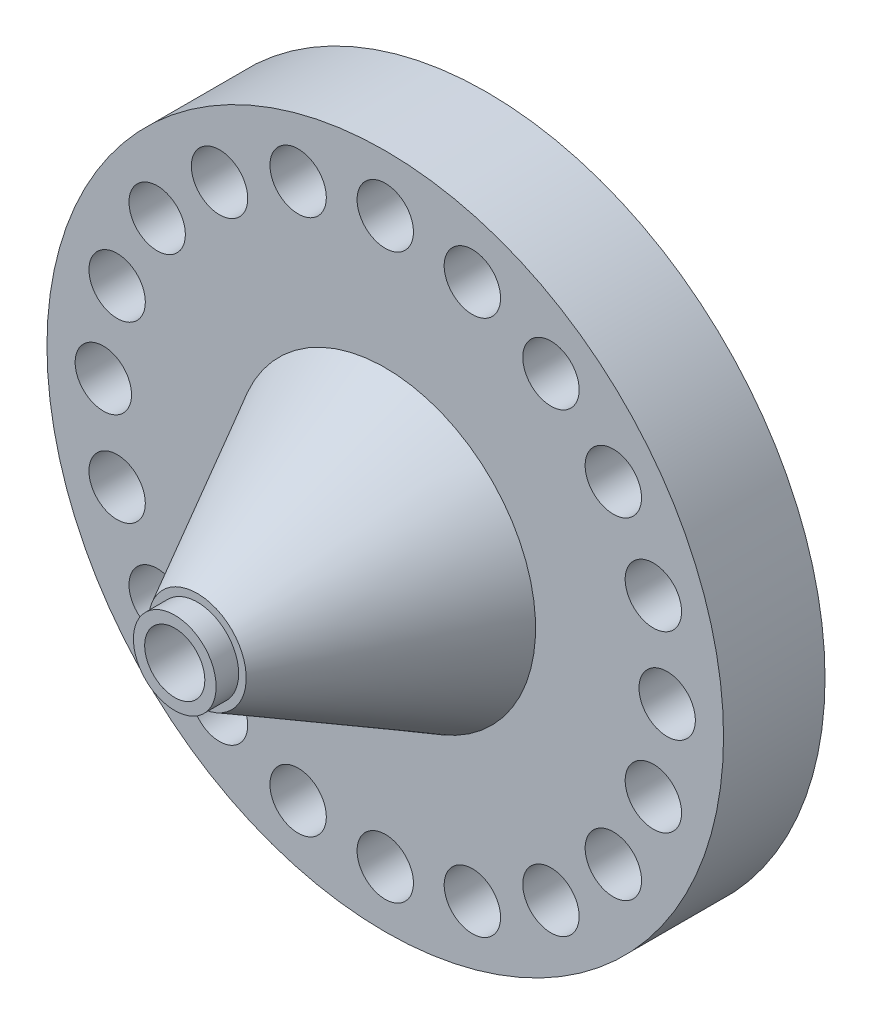
SolidWorks part; units mm, degrees
ref_plane "Front Plane" through (0, 0, 0) normal (0, 0, 1) x (1, 0, 0)
ref_plane "Top Plane" through (0, 0, 0) normal (0, 1, 0) x (1, 0, 0)
ref_plane "Right Plane" through (0, 0, 0) normal (1, 0, 0) x (0, 0, -1)
sketch "Sketch1" plane through (0, 0, 0) normal (0, 0, 1) x (1, 0, 0)
  circle A0 centre (0, 0) radius 45
  circle A1 centre (0, 0) radius 37.5 construction
  circle A2 centre (0, 37.5) radius 3.75
  circle A3 centre (11.5881, 35.6646) radius 3.75
  circle A4 centre (22.0419, 30.3381) radius 3.75
  circle A5 centre (30.3381, 22.0419) radius 3.75
  circle A6 centre (35.6646, 11.5881) radius 3.75
  circle A7 centre (37.5, 0) radius 3.75
  circle A8 centre (35.6646, -11.5881) radius 3.75
  circle A9 centre (30.3381, -22.0419) radius 3.75
  circle A10 centre (22.0419, -30.3381) radius 3.75
  circle A11 centre (11.5881, -35.6646) radius 3.75
  circle A12 centre (0, -37.5) radius 3.75
  circle A13 centre (-11.5881, -35.6646) radius 3.75
  circle A14 centre (-22.0419, -30.3381) radius 3.75
  circle A15 centre (-30.3381, -22.0419) radius 3.75
  circle A16 centre (-35.6646, -11.5881) radius 3.75
  circle A17 centre (-37.5, 0) radius 3.75
  circle A18 centre (-35.6646, 11.5881) radius 3.75
  circle A19 centre (-30.3381, 22.0419) radius 3.75
  circle A20 centre (-22.0419, 30.3381) radius 3.75
  circle A21 centre (-11.5881, 35.6646) radius 3.75
  dimension "D1" = 90
  dimension "D2" = 75
  dimension "D3" = 7.5
  dimension "D4" = 20
extrude "Boss-Extrude1" add sketch "Sketch1" along normal mid plane 13.5
sketch "Sketch2" plane through (0, 0, 6.75) normal (0, 0, 1) x (1, 0, 0)
  circle A0 centre (0, 0) radius 20
  dimension "D1" = 40
ref_plane "Plane1" through (0, 0, 31.75) normal (0, 0, 1) x (1, 0, 0)
sketch "Sketch3" plane through (0, 0, 31.75) normal (0, 0, 1) x (1, 0, 0)
  circle A0 centre (0, 0) radius 6.5
  dimension "D1" = 13
loft "Loft1" add profiles "Sketch3", "Sketch2"
sketch "Sketch5" plane through (0, 0, 31.75) normal (0, 0, 1) x (1, 0, 0)
  circle A0 centre (0, 0) radius 5.5
  dimension "D1" = 11
extrude "Boss-Extrude2" add sketch "Sketch5" along normal blind 3
sketch "Sketch6" plane through (0, 0, 34.75) normal (0, 0, 1) x (1, 0, 0)
  circle A0 centre (0, 0) radius 4
  dimension "D1" = 8
extrude "Cut-Extrude2" cut sketch "Sketch6" against normal through all
sketch "Sketch8" plane through (0, 0, -6.75) normal (0, 0, -1) x (-1, 0, 0)
  circle A0 centre (0, 0) radius 6
  dimension "D1" = 12
extrude "Cut-Extrude3" cut sketch "Sketch8" against normal blind 2
